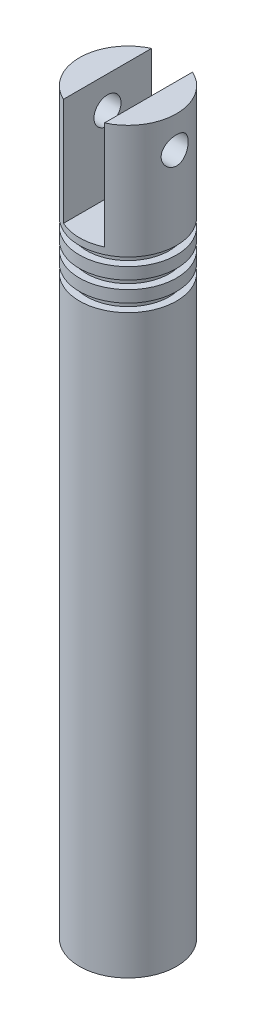
SolidWorks part; units mm, degrees
ref_plane "Front Plane" through (0, 0, 0) normal (0, 0, 1) x (1, 0, 0)
ref_plane "Top Plane" through (0, 0, 0) normal (0, 1, 0) x (1, 0, 0)
ref_plane "Right Plane" through (0, 0, 0) normal (1, 0, 0) x (0, 0, -1)
sketch "Sketch1" plane through (0, 0, 0) normal (0, 1, 0) x (1, 0, 0)
  circle A0 centre (0, 0) radius 5.5689
extrude "Boss-Extrude1" add sketch "Sketch1" along normal blind 84.6658
sketch "Sketch2" plane through (0, 84.6658, 0) normal (0, 1, 0) x (1, 0, 0)
  line L1 (-2.3495, -8.0657) -> (2.3495, -8.0657)
  line L2 (-2.3495, -8.0657) -> (-2.3495, 8.0657)
  line L3 (-2.3495, 8.0657) -> (2.3495, 8.0657)
  line L4 (2.3495, -8.0657) -> (2.3495, 8.0657)
  line L5 (-2.3495, -8.0657) -> (2.3495, 8.0657) construction
  line L6 (-2.3495, 8.0657) -> (2.3495, -8.0657) construction
  point P0 (0, 0)
  dimension "D1" = 4.699
extrude "Cut-Extrude1" cut sketch "Sketch2" against normal blind 12.319
sketch "Sketch3" plane through (0, 0, 0) normal (1, 0, 0) x (0, 0, -1)
  line L0 (5.0491, 84.6658) -> (-5.0491, 84.6658) construction
  circle A0 centre (0, 81.0336) radius 1.5494
  dimension "D2" = 3.0988
  dimension "D1" = 3.6322
extrude "Cut-Extrude2" cut sketch "Sketch3" against normal through all both and the other way through all
sketch "Sketch4" plane through (0, 0, 0) normal (1, 0, 0) x (0, 0, -1)
  line L0 (5.5689, 71.5838) -> (4.7251, 71.5838)
  line L1 (5.5689, 0) -> (5.5689, 72.3468) construction
  line L2 (4.7251, 71.5838) -> (4.7251, 70.6362)
  line L3 (4.7251, 70.6362) -> (5.5689, 70.6362)
  line L4 (5.5689, 70.6362) -> (5.5689, 71.5838)
ref_axis "Axis1" through (0, -4.2333, 0) along (0, 1, 0)
revolve "Cut-Revolve1" cut sketch "Sketch4" angle 360 about axis through (0, -4.2333, 0) along (0, 1, 0)
pattern_linear "LPattern1" count 3 spacing 2.286 along (0, -1, 0) of "Cut-Revolve1"
